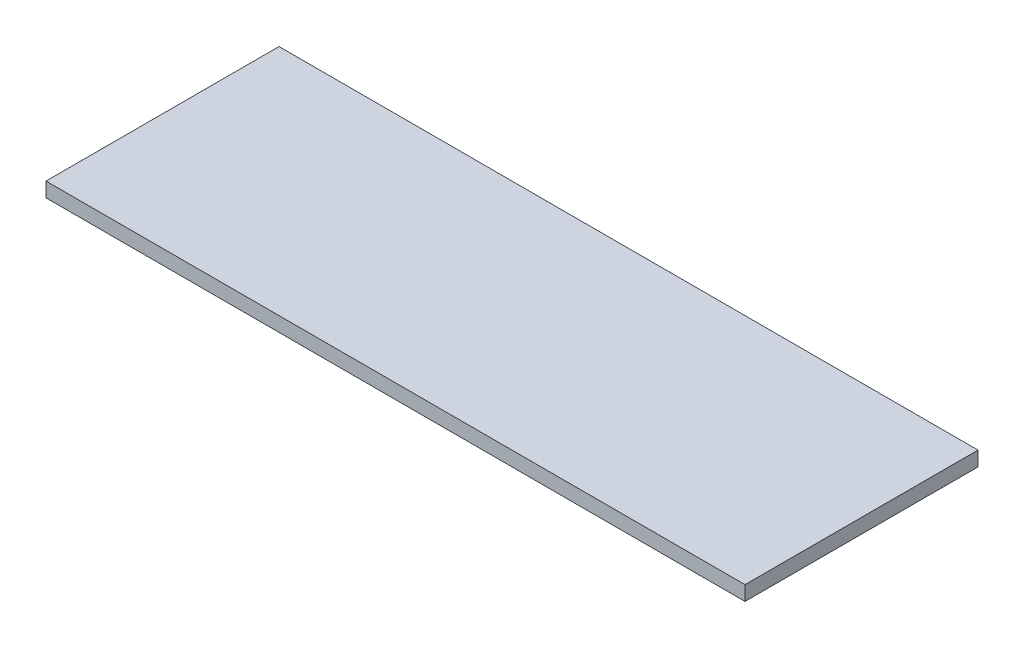
SolidWorks part; units mm, degrees
ref_plane "Front Plane" through (0, 0, 0) normal (0, 0, 1) x (1, 0, 0)
ref_plane "Top Plane" through (0, 0, 0) normal (0, 1, 0) x (1, 0, 0)
ref_plane "Right Plane" through (0, 0, 0) normal (1, 0, 0) x (0, 0, -1)
sketch "Sketch1" plane through (0, 0, 0) normal (0, 0, 1) x (1, 0, 0)
  line L1 (19.6889, 16.1056) -> (67.6889, 16.1056)
  line L2 (19.6889, 16.1056) -> (19.6889, 0.1056)
  line L3 (19.6889, 0.1056) -> (67.6889, 0.1056)
  line L4 (67.6889, 16.1056) -> (67.6889, 0.1056)
  line L5 (43.6889, 0.1056) -> (43.6889, 16.1056) construction
  line L6 (19.6889, 8.1056) -> (67.6889, 8.1056) construction
  point P104 (43.6889, 8.1056)
  dimension "D1" = 16
  dimension "D2" = 48
extrude "Boss-Extrude1" add sketch "Sketch1" along normal blind 1
move or copy body "Body-Move/Copy1" bodies to move or copy 102 copy no rotation origin (0, 8.1056, 0.25) rotation axis (1, 0, 0) rotation angle 90
